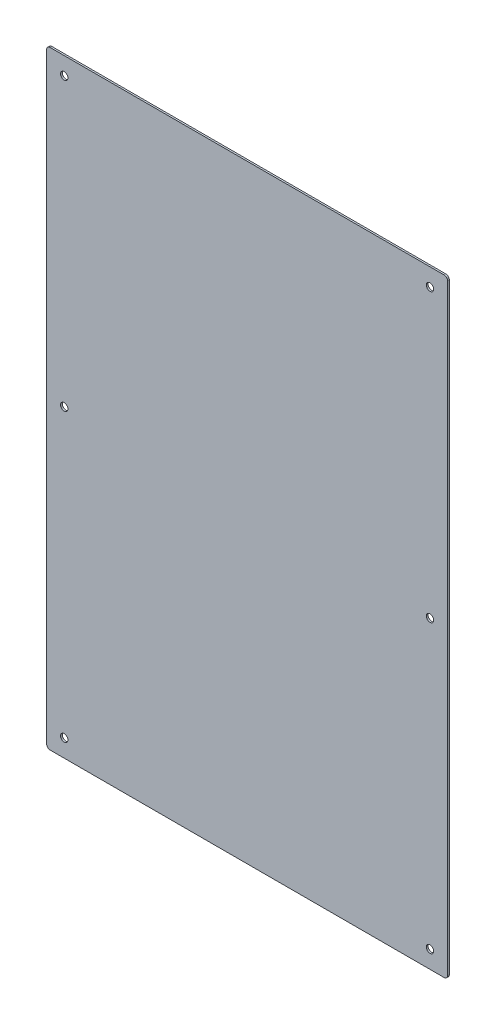
SolidWorks part; units mm, degrees
ref_plane "Спереди" through (0, 0, 0) normal (0, 0, 1) x (1, 0, 0)
ref_plane "Сверху" through (0, 0, 0) normal (0, 1, 0) x (1, 0, 0)
ref_plane "Справа" through (0, 0, 0) normal (1, 0, 0) x (0, 0, -1)
sketch "Эскиз1" plane through (0, 0, 0) normal (0, 0, 1) x (1, 0, 0)
  line L0 (-132.2991, 0) -> (40.0518, 0) construction
  line L1 (0, -29.1001) -> (0, 23.6764) construction
  line L3 (-112, -173) -> (112, -173)
  line L4 (-114, -171) -> (-114, 171)
  line L5 (-112, 173) -> (112, 173)
  line L6 (114, -171) -> (114, 171)
  circle A0 centre (-104, 163) radius 2.1
  circle A1 centre (-104, 0) radius 2.1
  circle A2 centre (-104, -163) radius 2.1
  circle A3 centre (104, -163) radius 2.1
  circle A4 centre (104, 0) radius 2.1
  circle A5 centre (104, 163) radius 2.1
  arc A6 (-114, 171) -> (-112, 173) centre (-112, 171) cw
  arc A7 (112, 173) -> (114, 171) centre (112, 171) cw
  arc A8 (112, -173) -> (114, -171) centre (112, -171) ccw
  arc A9 (-112, -173) -> (-114, -171) centre (-112, -171) cw
  point P23 (-114, 173)
  point P26 (114, 173)
  point P29 (114, -173)
  point P32 (-114, -173)
  dimension "D3" = 4.2
  dimension "D5" = 10
  dimension "D6" = 4.2
  dimension "D7" = 10
  dimension "D8" = 2
  dimension "D1" = 346
  dimension "D2" = 228
  dimension "D4" = 10
extrude "Вытянуть1" add sketch "Эскиз1" along normal blind 1
